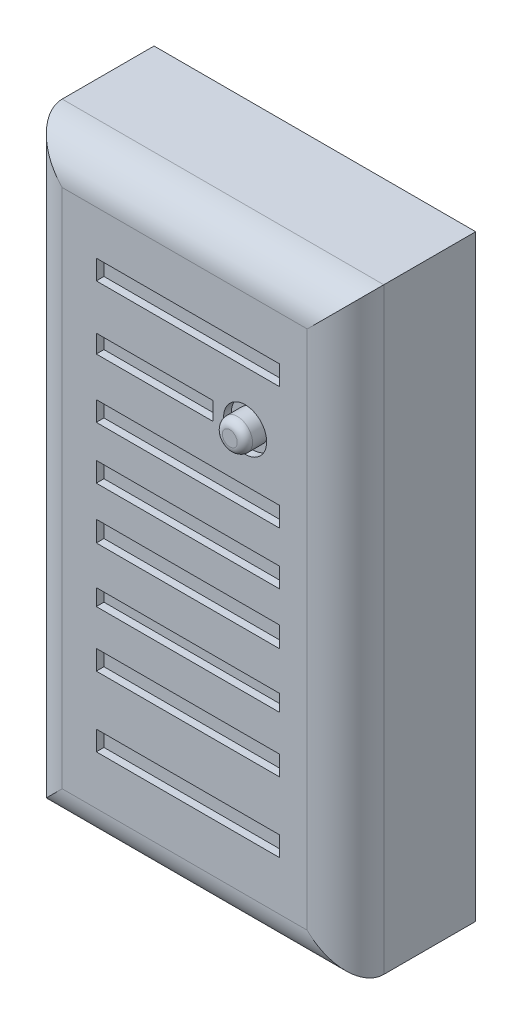
SolidWorks part; units mm, degrees
ref_plane "Спереди" through (0, 0, 0) normal (0, 0, 1) x (1, 0, 0)
ref_plane "Сверху" through (0, 0, 0) normal (0, 1, 0) x (1, 0, 0)
ref_plane "Справа" through (0, 0, 0) normal (1, 0, 0) x (0, 0, -1)
sketch "Эскиз1" plane through (0, 0, 0) normal (0, 0, 1) x (1, 0, 0)
  line L1 (-16.5506, 15.184) -> (25.4494, 15.184)
  line L2 (-16.5506, 15.184) -> (-16.5506, -62.816)
  line L3 (-16.5506, -62.816) -> (25.4494, -62.816)
  line L4 (25.4494, 15.184) -> (25.4494, -62.816)
  dimension "D1" = 42
  dimension "D2" = 78
extrude "Бобышка-Вытянуть1" add sketch "Эскиз1" along normal blind 17
fillet "Скругление1" radius 5 4 edges at (-16.5506, -23.816, 17) (4.4494, -62.816, 17) (25.4494, -23.816, 17) (4.4494, 15.184, 17)
sketch "Эскиз2" plane through (0, 0, 17) normal (0, 0, 1) x (1, 0, 0)
  line L1 (-7.0939, 4.4249) -> (16.8518, 4.4249)
  line L2 (-7.0939, 4.4249) -> (-7.0939, 1.8478)
  line L3 (-7.0939, 1.8478) -> (16.8518, 1.8478)
  line L4 (16.8518, 4.4249) -> (16.8518, 1.8478)
  line L5 (-7.0939, -4.0581) -> (8.154, -4.0581)
  line L6 (-7.0939, -4.0581) -> (-7.0939, -6.4205)
  line L7 (-7.0939, -6.4205) -> (8.154, -6.4205)
  line L8 (8.154, -4.0581) -> (8.154, -6.4205)
  line L9 (-7.0939, -11.5747) -> (16.8518, -11.5747)
  line L10 (-7.0939, -11.5747) -> (-7.0939, -14.1518)
  line L11 (-7.0939, -14.1518) -> (16.8518, -14.1518)
  line L12 (16.8518, -11.5747) -> (16.8518, -14.1518)
  line L13 (-7.0939, -18.447) -> (16.8518, -18.447)
  line L14 (-7.0939, -18.447) -> (-7.0939, -21.0241)
  line L15 (-7.0939, -21.0241) -> (16.8518, -21.0241)
  line L16 (16.8518, -18.447) -> (16.8518, -21.0241)
  line L17 (-7.0939, -25.1045) -> (16.8518, -25.1045)
  line L18 (-7.0939, -25.1045) -> (-7.0939, -27.789)
  line L19 (-7.0939, -27.789) -> (16.8518, -27.789)
  line L20 (16.8518, -25.1045) -> (16.8518, -27.789)
  line L21 (-7.0939, -32.8359) -> (16.8518, -32.8359)
  line L22 (-7.0939, -32.8359) -> (-7.0939, -34.9835)
  line L23 (-7.0939, -34.9835) -> (16.8518, -34.9835)
  line L24 (16.8518, -32.8359) -> (16.8518, -34.9835)
  line L25 (-7.0939, -39.7082) -> (16.8518, -39.7082)
  line L26 (-7.0939, -39.7082) -> (-7.0939, -42.2853)
  line L27 (-7.0939, -42.2853) -> (16.8518, -42.2853)
  line L28 (16.8518, -39.7082) -> (16.8518, -42.2853)
  line L29 (-7.0939, -48.8354) -> (16.8518, -48.8354)
  line L30 (-7.0939, -48.8354) -> (-7.0939, -51.4126)
  line L31 (-7.0939, -51.4126) -> (16.8518, -51.4126)
  line L32 (16.8518, -48.8354) -> (16.8518, -51.4126)
  circle A0 centre (12.3418, -5.2393) radius 2.8104
extrude "Вырез-Вытянуть1" cut sketch "Эскиз2" against normal blind 1
sketch "Эскиз3" plane through (0, 0, 16) normal (0, 0, 1) x (1, 0, 0)
  circle A0 centre (12.3418, -5.2393) radius 1.9712
extrude "Бобышка-Вытянуть2" add sketch "Эскиз3" along normal blind 3
fillet "Скругление2" radius 1 1 edges at (14.3131, -5.2393, 19)
